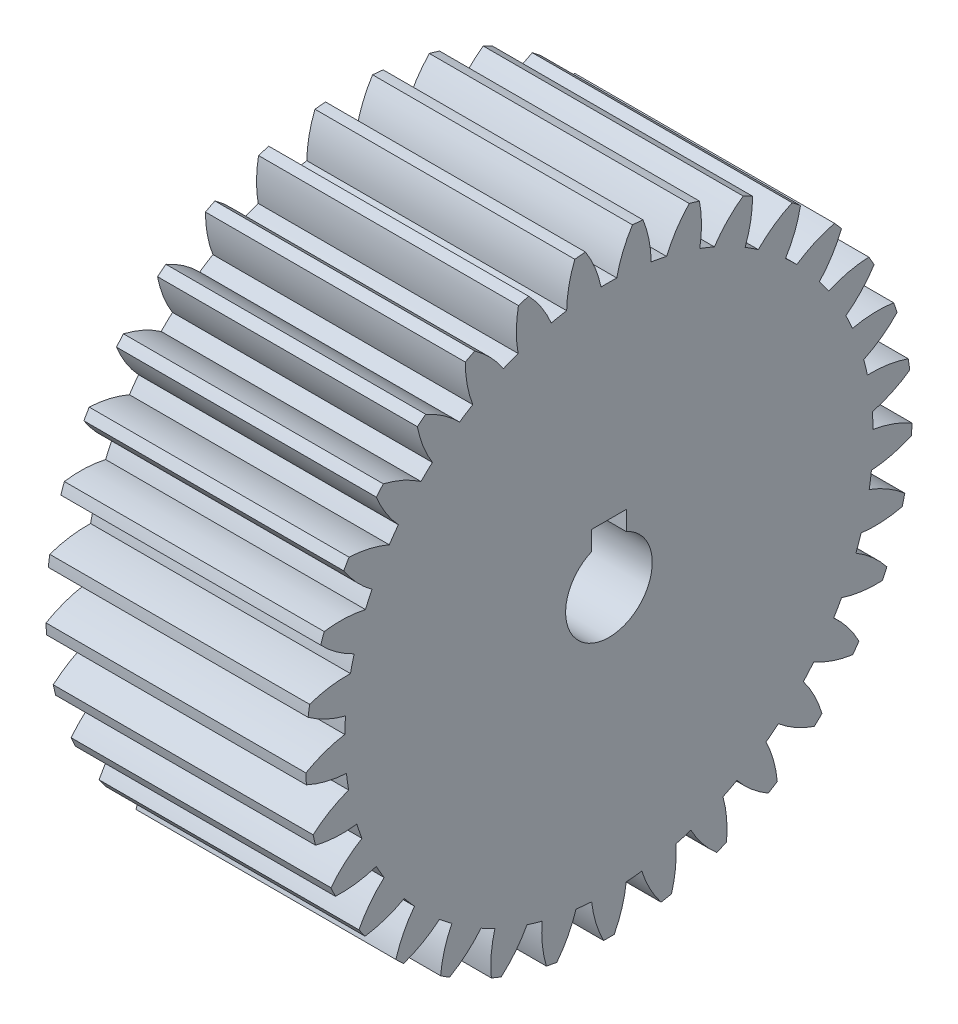
SolidWorks part; units mm, degrees
ref_plane "Plane1" through (0, 0, 0) normal (0, 0, 1) x (1, 0, 0)
ref_plane "Plane2" through (0, 0, 0) normal (0, 1, 0) x (1, 0, 0)
ref_plane "Plane3" through (0, 0, 0) normal (1, 0, 0) x (0, 0, -1)
sketch "HoldingSke" plane through (0, 0, 0) normal (0, 1, 0) x (1, 0, 0)
  line L0 (0, 0) -> (0.4193, -0.2723)
  line L1 (-15, 0) -> (100, 0) construction
  line L2 (0, 0) -> (-2.1039, 2.3779)
  line L3 (0, 0) -> (-11.863, 4.5341)
  line L4 (0, 0) -> (7.2428, 4.7035)
  line L5 (0, 0) -> (-46.8476, -17.4728)
  line L6 (0, 0) -> (-24.8689, -16.7791)
  line L7 (-2.1039, 2.3779) -> (8.6586, 51.2059)
  line L8 (-76.2, 54.61) -> (-74.4, 54.61)
  line L9 (-71.009, 38.7566) -> (-53.1078, 45.2721)
  line L10 (-76.2, 71.12) -> (104.1128, 71.12)
  line L11 (0, 0) -> (-30, 0)
  line L12 (-76.2, 101.6) -> (-76.133, 101.6)
  line L13 (24.9733, 27.94) -> (52.9518, 28.4284)
  line L14 (24.9733, 27.94) -> (24.9743, 27.94)
  line L15 (24.9733, 27.94) -> (100.4006, 29.5858)
  line L16 (-63.627, -2) -> (-12.827, -2)
  circle A0 centre (0, 0) radius 5
  circle A1 centre (0, 0) radius 30.499
  circle A2 centre (0, 0) radius 37.5
  circle A3 centre (0, 0) radius 5
  dimension "MHD" = 60.998
  dimension "Hub_dia" = 75
  dimension "Bore" = 10
  dimension "MBD" = 10
  dimension "Num_teeth" = 33
  dimension "Pitch" = 0.5
  dimension "Overall_len" = 50
  dimension "Show_teeth" = 33
  dimension "Thickness" = 30
  dimension "OAL" = 50.0001
  dimension "T_dim" = 1.8
  dimension "Ap" = 20
  dimension "H" = 19.05
  dimension "Pitch_radius" = 180.3128
  dimension "Width" = 30
  dimension "Backlash" = 0.067
  dimension "Addendum_fac" = 1
  dimension "Dedendum_fac" = 1.25
  dimension "Clearance_fac" = 0.25
  dimension "Dedendum_add" = 0.001
  dimension "Module" = 2
sketch "BasProSke" plane through (0, 0, 0) normal (0, 1, 0) x (1, 0, 0)
  line L0 (-10, 0) -> (60, 0) construction
  line L1 (0, 0) -> (0, 35)
  line L2 (0, 0) -> (30, 0)
  line L3 (30, 0) -> (30, 35)
  line L4 (30, 35) -> (0, 35)
  dimension "Thickness" = 30
  dimension "Diameter" = 70
revolve "Base-Revolve" add sketch "BasProSke" angle 360 about L0
sketch "TooCutSke" plane through (0, 0, 0) normal (1, 0, 0) x (0, 0, -1)
  line L1 (0, 0) -> (0, 107) construction
  line L2 (0, 0) -> (-1.6874, 32.9568) construction
  line L3 (0, 0) -> (-6.2676, 65.6374) construction
  line L4 (-1.6874, 32.9568) -> (-3.1338, 32.8187) construction
  arc A0 (0.9057, 30.4855) -> (-0.9057, 30.4855) centre (0, 0) ccw
  arc A1 (2.7313, 34.9187) -> (-2.7313, 34.9187) centre (0, 0) ccw
  circle A2 centre (0, 0) radius 33 construction
  circle A3 centre (0, 0) radius 31.0099 construction
  arc A4 (-0.9057, 30.4855) -> (-2.7313, 34.9187) centre (-13.8212, 27.7594) ccw
  arc A5 (2.7313, 34.9187) -> (0.9057, 30.4855) centre (13.8212, 27.7594) ccw
  dimension "Root_dia" = 60.998
  dimension "Overcut_dia" = 70.0508
  dimension "Pitch_dia" = 66
  dimension "Base_dia" = 62.0197
  dimension "Flank_rad" = 13.2
  dimension "Half_ang" = 5.455
  dimension "Half_CT" = 1.453
extrude "ToothCut" cut sketch "TooCutSke" along normal through all
fillet "Breaks" [suppressed] radius 0.04
fillet "RootFillets" [suppressed] radius 0.501
pattern_circular "TeethCuts" count 33 every 10.909 about axis through (-10, 0, 0) along (1, 0, 0) of "ToothCut", "RootFillets", "Breaks"
sketch "HubNeaOneSke" plane through (0, 0, 0) normal (-1, 0, 0) x (0, 0, 1)
  circle A0 centre (0, 0) radius 30.499
  dimension "Diameter" = 60.998
extrude "HubNearOne" [suppressed] add sketch "HubNeaOneSke" along normal blind 20.0001
sketch "HubNeaBotSke" plane through (0, 0, 0) normal (-1, 0, 0) x (0, 0, 1)
  circle A0 centre (0, 0) radius 30.499
  dimension "Diameter" = 60.998
extrude "HubNearBoth" [suppressed] add sketch "HubNeaBotSke" along normal blind 10
ref_plane "FarPln" through (30, 0, 0) normal (1, 0, 0) x (0, 0, -1)
sketch "HubFarSke" plane through (30, 0, 0) normal (1, 0, 0) x (0, 0, -1)
  circle A0 centre (0, 0) radius 30.499
  dimension "Diameter" = 60.998
extrude "HubFar" [suppressed] add sketch "HubFarSke" along normal blind 10
sketch "BorSke" plane through (0, 0, 0) normal (1, 0, 0) x (0, 0, -1)
  circle A0 centre (0, 0) radius 5
  dimension "Diameter" = 10
extrude "Bore" cut sketch "BorSke" along normal mid plane 100.0001
sketch "KeySke" plane through (0, 0, 0) normal (1, 0, 0) x (0, 0, -1)
  line L0 (-2, 0) -> (-2, 6.8)
  line L1 (-2, 6.8) -> (2, 6.8)
  line L2 (2, 6.8) -> (2, 0)
  line L3 (0, 0) -> (0, 34) construction
  line L4 (-2, 0) -> (2, 0)
  dimension "Offset" = 6.8
  dimension "Width" = 4
extrude "Keyway" cut sketch "KeySke" along normal mid plane 100.0001
pattern_circular "Keyway2" [suppressed] count 2 every 90 about axis through (-10, 0, 0) along (1, 0, 0)
equation "' \"Module@HoldingSke\" = 6.35"
equation "' \"Num_teeth@HoldingSke\" = 12"
equation "' \"Ap@HoldingSke\" =  20"
equation "' \"Ap@HoldingSke\" = 20"
equation "' \"Width@HoldingSke\" = 0.5 * 25.4"
equation "' \"Hub_dia@HoldingSke\"= 1 * 25.4"
equation "' \"Hub_dia@HoldingSke\" = 1 * 25.4"
equation "' \"Overall_len@HoldingSke\" = 1.0 * 25.4"
equation "' \"Bore@HoldingSke\" = 0.75 * 25.4"
equation "' \"T_dim@HoldingSke\" = 0.1 * 25.4"
equation "' \"Width@KeySke\" = 0.25 * 25.4"
equation "' \"Show_teeth@HoldingSke\" = 13"
equation "' \"Backlash@HoldingSke\" = 0.009 * 25.4"
equation "' \"Addendum_fac@HoldingSke\" = 1.0"
equation "' \"Dedendum_fac@HoldingSke\" = 1.25"
equation "' \"Dedendum_add@HoldingSke\" = 0.00005 * 25.4"
equation "' \"Clearance_fac@HoldingSke\" = 0.25"
equation "\"Pitch@HoldingSke\" = 1 / \"Module@HoldingSke\""
equation "\"Overcut_dia@TooCutSke\" = (\"Num_teeth@HoldingSke\" + 2 * \"Addendum_fac@HoldingSke\") / \"Pitch@HoldingSke\" + 0.002 * 25.4"
equation "\"Pitch_dia@TooCutSke\" = \"Num_teeth@HoldingSke\" / \"Pitch@HoldingSke\""
equation "\"Base_dia@TooCutSke\" = \"Num_teeth@HoldingSke\" / \"Pitch@HoldingSke\" * cos((\"Ap@HoldingSke\"  * 3.14159265 / 180))"
equation "\"Root_dia@TooCutSke\" = (\"Num_teeth@HoldingSke\" + 2) / \"Pitch@HoldingSke\" - 2 * (\"Addendum_fac@HoldingSke\" + \"Dedendum_fac@HoldingSke\") / \"Pitch@HoldingSke\" - \"Dedendum_add@HoldingSke\" * 2"
equation "\"Half_ang@TooCutSke\" = 180 / \"Num_teeth@HoldingSke\""
equation "\"Half_CT@TooCutSke\" = \"Num_teeth@HoldingSke\" / \"Pitch@HoldingSke\" * sin((3.14159265 / 2 / \"Num_teeth@HoldingSke\")) / 2 - 7 * \"Backlash@HoldingSke\" / 4"
equation "\"Flank_rad@TooCutSke\" = \"Num_teeth@HoldingSke\" / \"Pitch@HoldingSke\" / 5"
equation "\"Radius@RootFillets\" = \"Clearance_fac@HoldingSke\" / \"Pitch@HoldingSke\" + \"Dedendum_add@HoldingSke\""
equation "\"Break_rad@Breaks\" = 0.02 / \"Pitch@HoldingSke\""
equation "\"Thickness@HoldingSke\" = \"Width@HoldingSke\""
equation "\"OAL@HoldingSke\" = \"Thickness@HoldingSke\""
equation "\"MHD@HoldingSke\" = (\"Num_teeth@HoldingSke\" + 2) / \"Pitch@HoldingSke\" - 2 * (\"Addendum_fac@HoldingSke\" + \"Dedendum_fac@HoldingSke\")  / \"Pitch@HoldingSke\" - \"Dedendum_add@HoldingSke\" * 2"
equation "\"MBD@HoldingSke\" = (\"Num_teeth@HoldingSke\" + 2) / \"Pitch@HoldingSke\" - 2 * (\"Addendum_fac@HoldingSke\" + \"Dedendum_fac@HoldingSke\")  / \"Pitch@HoldingSke\" - \"Dedendum_add@HoldingSke\" * 2 - 0.002 * 25.4"
equation "\"MHD@HoldingSke\" = ((sgn( \"MHD@HoldingSke\" - \"Hub_dia@HoldingSke\" )-1)*( \"MHD@HoldingSke\" - \"Hub_dia@HoldingSke\" ))/-2+ \"Hub_dia@HoldingSke\""
equation "\"MBD@HoldingSke\" = ((sgn( \"MBD@HoldingSke\" - \"Bore@HoldingSke\" )-1)*( \"MBD@HoldingSke\" - \"Bore@HoldingSke\" ))/-2+ \"Bore@HoldingSke\""
equation "\"OAL@HoldingSke\" = ((sgn( \"OAL@HoldingSke\" - \"Overall_len@HoldingSke\" )+1)*( \"OAL@HoldingSke\" - \"Overall_len@HoldingSke\" ))/2 + \"Overall_len@HoldingSke\" + 0.000002 * 25.4"
equation "\"Num_teeth@TeethCuts\" = int( \"Show_teeth@HoldingSke\" ) + 1"
equation "\"Num_teeth@TeethCuts\" = ((sgn( \"Num_teeth@TeethCuts\" - \"Num_teeth@HoldingSke\" )-1)*( \"Num_teeth@TeethCuts\" - \"Num_teeth@HoldingSke\" ))/-2+ \"Num_teeth@HoldingSke\""
equation "\"Num_teeth@TeethCuts\" = ((sgn( \"Num_teeth@TeethCuts\" - 2.0)+1)*( \"Num_teeth@TeethCuts\" - 2.0))/2 +2.0"
equation "\"Angle@TeethCuts\" = 360.0 / \"Num_teeth@HoldingSke\""
equation "\"Diameter@BasProSke\" = (\"Num_teeth@HoldingSke\" + 2 * \"Addendum_fac@HoldingSke\") / \"Pitch@HoldingSke\""
equation "\"Thickness@BasProSke\"  = \"Thickness@HoldingSke\""
equation "' \"Fillet_rad@BasProSke\" =  \"Thickness@HoldingSke\" * 0.05"
equation "' \"Fillet_rad@BasProSke\" = \"Thickness@HoldingSke\" * 0.05"
equation "\"MHD@HoldingSke\" = ((sgn( \"MHD@HoldingSke\" - \"Root_dia@TooCutSke\" )-1)*( \"MHD@HoldingSke\" - \"Root_dia@TooCutSke\" ))/-2+ \"Root_dia@TooCutSke\""
equation "\"Diameter@HubNeaOneSke\" = \"MHD@HoldingSke\""
equation "\"Length@HubNearOne\" = \"OAL@HoldingSke\" - \"Thickness@BasProSke\""
equation "\"Diameter@HubNeaBotSke\" = \"MHD@HoldingSke\""
equation "\"Length@HubNearBoth\" = ( \"OAL@HoldingSke\" - \"Thickness@BasProSke\" ) / 2.0"
equation "\"Thickness@FarPln\" = \"Thickness@BasProSke\""
equation "\"Diameter@HubFarSke\" = \"MHD@HoldingSke\""
equation "\"Length@HubFar\" = ( \"OAL@HoldingSke\" - \"Thickness@BasProSke\" ) / 2.0"
equation "\"Diameter@BorSke\" = \"MBD@HoldingSke\""
equation "\"D1@Bore\" = \"OAL@HoldingSke\" * 2.0"
equation "\"D1@Keyway\" = \"OAL@HoldingSke\" * 2.0"
equation "\"Offset@KeySke\" = \"T_dim@HoldingSke\" + \"MBD@HoldingSke\" / 2.0"
